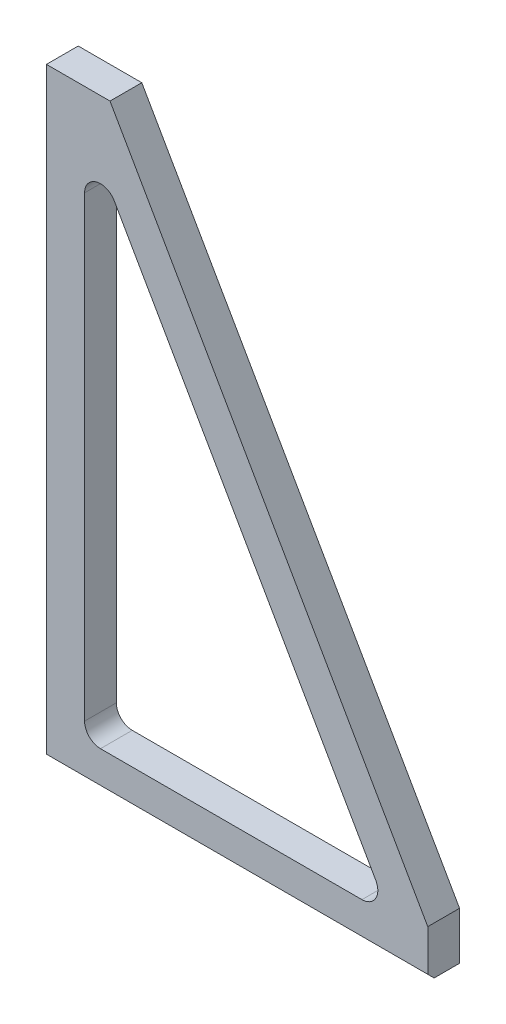
SolidWorks part; units mm, degrees
ref_plane "Front" through (0, 0, 0) normal (0, 0, 1) x (1, 0, 0)
ref_plane "Top" through (0, 0, 0) normal (0, 1, 0) x (1, 0, 0)
ref_plane "Right" through (0, 0, 0) normal (1, 0, 0) x (0, 0, -1)
other "Configuration Table"
sketch "Sketch1" plane through (0, 0, 0) normal (0, 0, 1) x (1, 0, 0)
  line L0 (15.24, 21.59) -> (15.24, 204.4515)
  line L1 (0, 0) -> (152.4, 0)
  line L2 (0, 0) -> (0, 241.3)
  line L3 (0, 241.3) -> (25.4, 241.3)
  line L4 (152.4, 0) -> (152.4, 19.05)
  line L7 (21.59, 15.24) -> (126.0823, 15.24)
  line L8 (25.4, 241.3) -> (152.4, 19.05)
  line L9 (27.1033, 207.6019) -> (131.5956, 24.7405)
  arc A0 (131.5956, 24.7405) -> (126.0823, 15.24) centre (126.0823, 21.59) cw
  arc A3 (15.24, 21.59) -> (21.59, 15.24) centre (21.59, 21.59) ccw
  arc A4 (15.24, 204.4515) -> (27.1033, 207.6019) centre (21.59, 204.4515) cw
  dimension "D4" = 6.35
  dimension "D8" = 6.35
  dimension "D9" = 6.35
  dimension "D1" = 152.4
  dimension "D2" = 241.3
  dimension "D5" = 19.05
  dimension "D6" = 25.4
  dimension "D3" = 15.24
  dimension "D7" = 15.24
extrude "Base-Extrude" add sketch "Sketch1" along normal blind 12.7
chamfer "Chamfer2" distance 2.54 angle 45 1 edges at (76.2, 0, 12.7)
